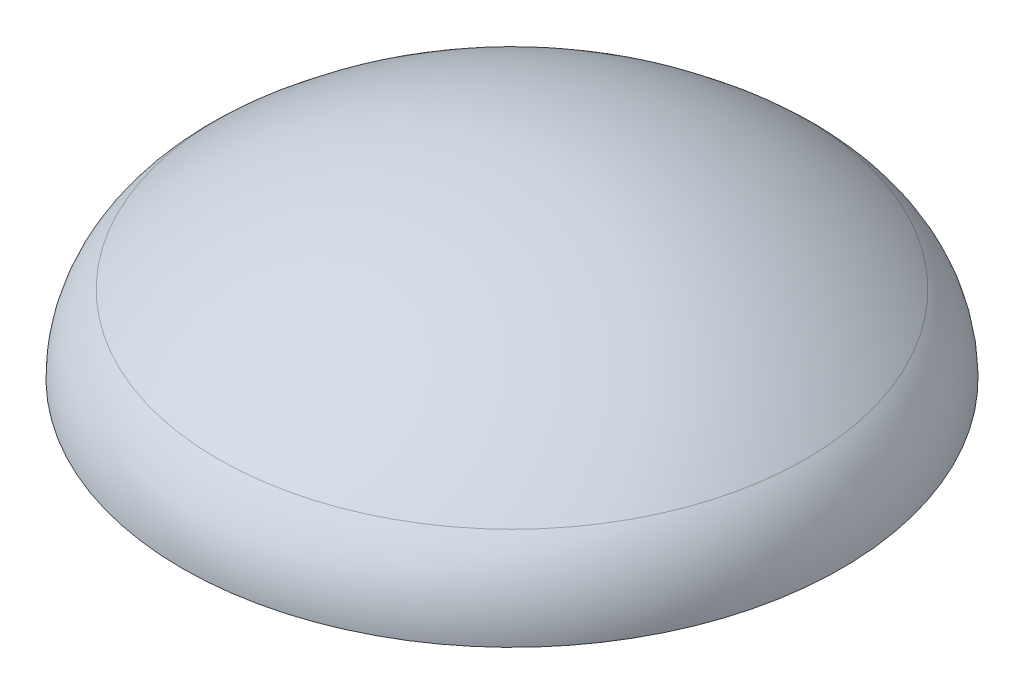
SolidWorks part; units mm, degrees
material "АД0 ГОСТ 4784-97"
ref_plane "Спереди" through (0, 0, 0) normal (0, 0, 1) x (1, 0, 0)
ref_plane "Сверху" through (0, 0, 0) normal (0, 1, 0) x (1, 0, 0)
ref_plane "Справа" through (0, 0, 0) normal (1, 0, 0) x (0, 0, -1)
sketch "Эскиз1" plane through (0, 0, 0) normal (0, 0, 1) x (1, 0, 0)
  line L0 (0, 39.365) -> (0, 36.365)
  line L1 (66.85, 0) -> (69.85, 0)
  line L2 (0, 69.552) -> (0, 0) construction
  arc A0 (0, 39.365) -> (62.3196, 16.3495) centre (0, -56.515) cw
  arc A1 (0, 36.365) -> (60.3697, 14.0697) centre (0, -56.515) cw
  arc A2 (60.3697, 14.0697) -> (66.85, 0) centre (48.3362, 0) cw
  arc A3 (62.3196, 16.3495) -> (69.85, 0) centre (48.3362, 0) cw
revolve "Повернуть1" add sketch "Эскиз1" angle 360 about L2
